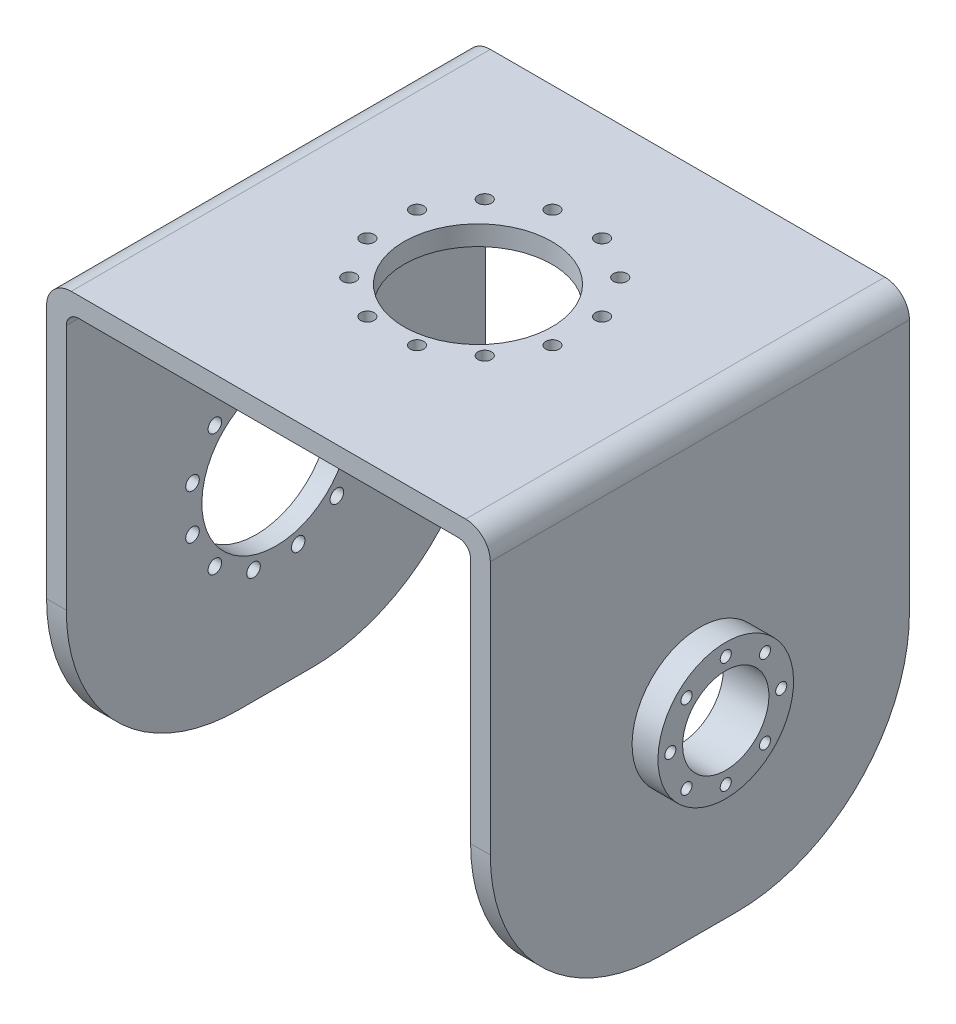
SolidWorks part; units mm, degrees
material "6061 合金"
ref_plane "前视基准面" through (0, 0, 0) normal (0, 0, 1) x (1, 0, 0)
ref_plane "上视基准面" through (0, 0, 0) normal (0, 1, 0) x (1, 0, 0)
ref_plane "右视基准面" through (0, 0, 0) normal (1, 0, 0) x (0, 0, -1)
other "Configuration Table"
sketch "草图1" plane through (0, 0, 0) normal (0, 0, 1) x (1, 0, 0)
  line L0 (-164, 0) -> (0, 0)
  line L1 (0, 0) -> (0, -175)
  line L3 (8, -175) -> (8, 8)
  line L4 (8, 8) -> (-164, 8)
  line L6 (0, -175) -> (8, -175)
  line L12 (-164, 8) -> (-172, 8)
  line L13 (-164, 0) -> (-164, -175)
  line L14 (-164, -175) -> (-172, -175)
  line L15 (-172, 8) -> (-172, -175)
  dimension "D1" = 8
  dimension "D2" = 8
  dimension "D3" = 180
  dimension "D5" = 183
  dimension "D6" = 8
  dimension "D8" = 8
extrude "凸台-拉伸1" add sketch "草图1" along normal blind 170
sketch "草图2" plane through (0, 8, 0) normal (0, 1, 0) x (1, 0, 0)
  line L0 (-216.3195, -85) -> (51.5119, -85) construction
  line L1 (8, -170) -> (-172, -170) construction
  line L2 (8, 0) -> (-172, 0) construction
  line L7 (-82, -75.3242) -> (-82, -92.2023) construction
  line L8 (8, -170) -> (8, 0) construction
  line L9 (-172, -170) -> (-172, 0) construction
  circle A2 centre (-82, -85) radius 30
  dimension "D3" = 60
extrude "切除-拉伸1" cut sketch "草图2" against normal blind 180 contours A2 L0 | L0 A2
sketch "草图3" plane through (8, 0, 0) normal (1, 0, 0) x (0, 0, -1)
  line L0 (-85, 25.6845) -> (-85, -173.3318) construction
  line L1 (0, -175) -> (0, 8) construction
  line L2 (-170, -175) -> (-170, 8) construction
  line L3 (-170, -175) -> (0, -175) construction
  line L4 (0, 0) -> (-209.686, 0) construction
  circle A0 centre (-85, -95) radius 17.5
  dimension "D1" = 35
  dimension "D2" = 80
extrude "切除-拉伸2" cut sketch "草图3" against normal through all both and the other way through all contours A0
fillet "圆角1" radius 70 4 edges at (-168, -175, 170) (-168, -175, 0) (4, -175, 0) (4, -175, 170)
fillet "圆角2" radius 5 2 edges at (-164, 0, 85) (0, 0, 85)
fillet "圆角3" radius 10 2 edges at (8, 8, 85) (-172, 8, 85)
sketch "草图6" plane through (-172, 0, 0) normal (-1, 0, 0) x (0, 0, 1)
  circle A0 centre (85, -95) radius 30
  dimension "D1" = 60
extrude "切除-拉伸6" cut sketch "草图6" against normal blind 39
sketch "草图7" plane through (0, 0, 0) normal (-1, 0, 0) x (0, 0, 1)
  circle A0 centre (85, -95) radius 13
  dimension "D1" = 26
extrude "切除-拉伸7" [suppressed] cut sketch "草图7" against normal blind 0.7
sketch "草图8" plane through (8, 0, 0) normal (1, 0, 0) x (0, 0, -1)
  line L0 (-85, -95) -> (-13.3452, -95) construction
  line L1 (-85, -95) -> (-143.0331, -95) construction
  circle A0 centre (-55, -95) radius 2.5
  circle A1 centre (-115, -95) radius 2.5
  dimension "D1" = 5
  dimension "D2" = 5
  dimension "D3" = 30
  dimension "D4" = 30
extrude "切除-拉伸8" [suppressed] cut sketch "草图8" against normal blind 10
sketch "草图9" [suppressed] plane through (8, 0, 0) normal (1, 0, 0) x (0, 0, -1)
  circle A0 centre (-55, -95) radius 6
  circle A1 centre (-115, -95) radius 6
  dimension "D1" = 12
  dimension "D2" = 12
extrude "切除-拉伸9" [suppressed] cut sketch "草图9" against normal blind 4
sketch "草图12" plane through (-172, 0, 0) normal (-1, 0, 0) x (0, 0, 1)
  line L0 (85, -95) -> (85, -143.8801) construction
  line L1 (85, -95) -> (97.9809, -143.4455) construction
  circle A0 centre (94.0587, -128.8074) radius 2.75
  circle A1 centre (75.9413, -128.8074) radius 2.75
  circle A2 centre (60.2513, -119.7487) radius 2.75
  circle A3 centre (51.1926, -104.0587) radius 2.75
  circle A4 centre (51.1926, -85.9413) radius 2.75
  circle A5 centre (60.2513, -70.2513) radius 2.75
  circle A6 centre (75.9413, -61.1926) radius 2.75
  circle A7 centre (94.0587, -61.1926) radius 2.75
  circle A8 centre (109.7487, -70.2513) radius 2.75
  circle A9 centre (118.8074, -85.9413) radius 2.75
  circle A10 centre (118.8074, -104.0587) radius 2.75
  circle A11 centre (109.7487, -119.7487) radius 2.75
  point P31 (85, -95)
  dimension "D2" = 5.5
  dimension "D1" = 15
  dimension "D3" = 35
  dimension "D4" = 12
extrude "切除-拉伸12" cut sketch "草图12" against normal blind 10
sketch "草图14" plane through (8, 0, 0) normal (1, 0, 0) x (0, 0, -1)
  circle A0 centre (-85, -95) radius 27.5
  circle A1 centre (-85, -95) radius 17.5 construction
  circle A2 centre (-85, -95) radius 17.5
  dimension "D1" = 55
extrude "凸台-拉伸2" add sketch "草图14" along normal blind 10.5
sketch "草图13" plane through (8, 0, 0) normal (1, 0, 0) x (0, 0, -1)
  line L0 (-85, -95) -> (-85, -50) construction
  circle A0 centre (-85, -95) radius 22.5 construction
  circle A1 centre (-85, -72.5) radius 2.25
  circle A2 centre (-69.0901, -79.0901) radius 2.25
  circle A3 centre (-62.5, -95) radius 2.25
  circle A4 centre (-69.0901, -110.9099) radius 2.25
  circle A5 centre (-85, -117.5) radius 2.25
  circle A6 centre (-100.9099, -110.9099) radius 2.25
  circle A7 centre (-107.5, -95) radius 2.25
  circle A8 centre (-100.9099, -79.0901) radius 2.25
  point P22 (-85, -95)
  dimension "D1" = 45
  dimension "D2" = 4.5
  dimension "D3" = 8
extrude "切除-拉伸13" cut sketch "草图13" against normal mid plane 30
sketch "草图15" plane through (0, 8, 0) normal (0, 1, 0) x (1, 0, 0)
  line L0 (-82, -85) -> (-82, -144.7778) construction
  line L1 (-82, -85) -> (-72.9413, -118.8074) construction
  circle A0 centre (-72.9413, -118.8074) radius 2.75
  circle A1 centre (-93.0587, -118.8074) radius 2.75
  circle A2 centre (-110.4808, -108.7487) radius 2.75
  circle A3 centre (-120.5395, -91.3266) radius 2.75
  circle A4 centre (-120.5395, -71.2093) radius 2.75
  circle A5 centre (-110.4808, -53.7872) radius 2.75
  circle A6 centre (-93.0587, -43.7285) radius 2.75
  circle A7 centre (-72.9413, -43.7285) radius 2.75
  circle A8 centre (-55.5192, -53.7872) radius 2.75
  circle A9 centre (-45.4605, -71.2093) radius 2.75
  circle A10 centre (-45.4605, -91.3266) radius 2.75
  circle A11 centre (-55.5192, -108.7487) radius 2.75
  point P29 (-83, -81.2679)
  dimension "D1" = 5.5
  dimension "D2" = 35
  dimension "D3" = 15
  dimension "D4" = 12
extrude "切除-拉伸14" cut sketch "草图15" against normal blind 10
